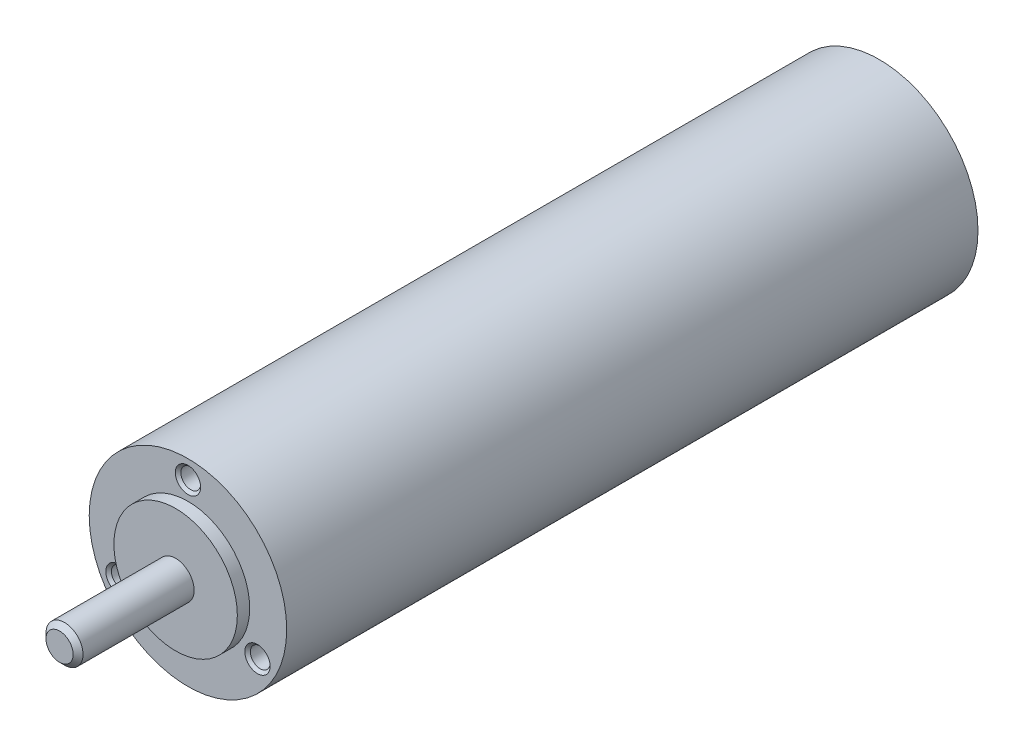
SolidWorks part; units mm, degrees
ref_plane "Спереди" through (0, 0, 0) normal (0, 0, 1) x (1, 0, 0)
ref_plane "Сверху" through (0, 0, 0) normal (0, 1, 0) x (1, 0, 0)
ref_plane "Справа" through (0, 0, 0) normal (1, 0, 0) x (0, 0, -1)
sketch "Эскиз1" plane through (0, 0, 0) normal (1, 0, 0) x (0, 0, -1)
  line L0 (0, 0) -> (66.4, 0) construction
  line L1 (0, 0) -> (0, -1.5)
  line L2 (0, -1.5) -> (9.4, -1.5)
  line L3 (9.4, -1.5) -> (9.4, -5)
  line L4 (9.4, -5) -> (10.4, -5)
  line L5 (10.4, -5) -> (10.4, -8)
  line L6 (10.4, -8) -> (66.4, -8)
  line L7 (66.4, -8) -> (66.4, 0)
  line L8 (0, 0) -> (66.4, 0)
  dimension "D1" = 3
  dimension "D2" = 10
  dimension "D3" = 16
  dimension "D4" = 56
  dimension "D5" = 10.4
  dimension "D6" = 1
revolve "Повернуть1" add sketch "Эскиз1" angle 360 about L0
chamfer "Фаска1" distance 0.4 1 edges at (1.5, 0, 0)
hole_wizard "Отверстие обработанное метчиком M2x0.41" positions "Эскиз4" profile "Эскиз5" tap size "M2x0.4" standard "Ansi Metric"
sketch "Эскиз4" plane through (0, 0, -10.4) normal (0, 0, 1) x (1, 0, 0)
  circle A0 centre (0, 0) radius 6.5 construction
  point P0 (0, 6.5)
  point P7 (0, 0)
  point P8 (0, 0)
  dimension "D1" = 13
sketch "Эскиз5" plane through (0, 6.5, -10.4) normal (1, 0, 0) x (0, -1, 0)
  line L0 (0, 0) -> (0, 4.4807)
  line L1 (0, 4.4807) -> (0.8, 4)
  line L2 (0.8, 4) -> (0.8, 0.225)
  line L3 (0.8, 0.225) -> (1.025, 0)
  line L5 (1.025, 0) -> (0, 0)
  line L6 (-0.8, 0.225) -> (-1.025, 0) construction
  line L10 (0, 4.4807) -> (-0.8, 4) construction
  line L11 (0, -6.35) -> (0, 107.95) construction
  dimension "Диаметр сверла" = 1.6
  dimension "Глубина сверла" = 4
  dimension "Диаметр передней зенковки" = 2.05
  dimension "Угол передней зенковки" = 90
  dimension "Угол заточки сверла" = 118
cosmetic thread "Отверстие резьбы1" parameters "D1"=3.5, "D2"=2
pattern_circular "Круговой массив1" count 3 over 360 about axis through (0, 0, 0) along (0, 0, 1) of "Отверстие обработанное метчиком M2x0.41"
